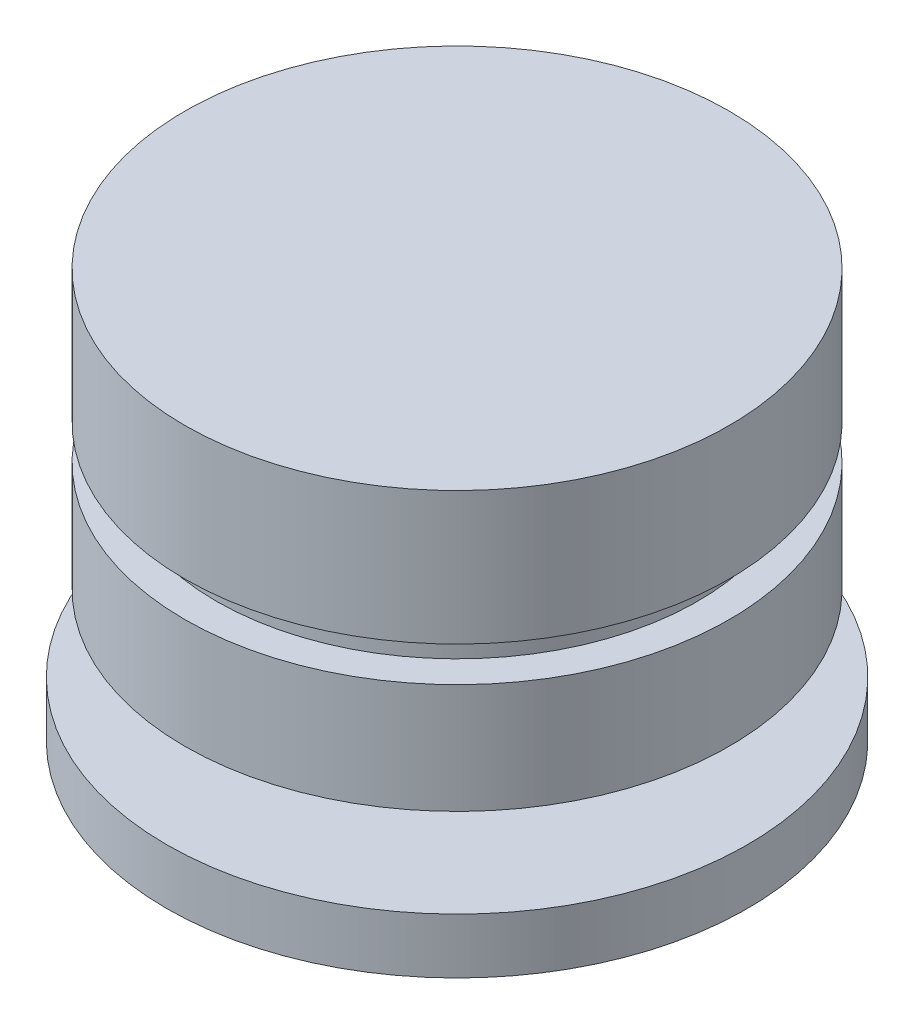
SolidWorks part; units mm, degrees
material "7075-T6 (SN)"
ref_plane "X-Y Datum" through (0, 0, 0) normal (0, 0, 1) x (1, 0, 0)
ref_plane "X-Z Datum" through (0, 0, 0) normal (0, 1, 0) x (1, 0, 0)
ref_plane "Y-Z Datum" through (0, 0, 0) normal (1, 0, 0) x (0, 0, -1)
sketch3d "3DSketch1"
  line L0 (0, 0, 0) -> (0, 50000, 0) construction
sketch "Mounting Plate SKETCH" plane through (0, 0, 0) normal (0, 1, 0) x (1, 0, 0)
  circle A0 centre (0, 0) radius 52.5
  dimension "mounting plate" = 105
extrude "Mount Plate" add sketch "Mounting Plate SKETCH" along normal blind 10
sketch "Hub-Rim Seat SKETCH" plane through (0, 0, 0) normal (0, -1, 0) x (1, 0, 0)
  circle A0 centre (0, 0) radius 27.435
  dimension "D1" = 54.87
sketch "Sketch7" plane through (0, 10, 0) normal (0, 1, 0) x (1, 0, 0)
  circle A0 centre (0, 0) radius 25.4
  dimension "D1" = 50.8
extrude "Boss-Extrude5" add sketch "Sketch7" along normal blind 13.749
sketch "Sketch6" [suppressed] plane through (0, 23.749, 0) normal (0, 1, 0) x (1, 0, 0)
  line L2 (0, -1000) -> (0, 49000) construction
  line L3 (-1000, 0) -> (49000, 0) construction
  line L20 (7.62, -45.2633) -> (12.7, -45.2633)
  line L21 (-7.62, -45.2633) -> (-12.7, -45.2633)
  line L22 (-43.0092, -16.0325) -> (-45.5492, -11.6331)
  line L23 (-35.3892, -29.2308) -> (-32.8492, -33.6302)
  line L24 (-35.3892, 29.2308) -> (-32.8492, 33.6302)
  line L25 (-43.0092, 16.0325) -> (-45.5492, 11.6331)
  line L26 (7.62, 45.2633) -> (12.7, 45.2633)
  line L27 (-7.62, 45.2633) -> (-12.7, 45.2633)
  line L28 (43.0092, 16.0325) -> (45.5492, 11.6331)
  line L29 (35.3892, 29.2308) -> (32.8492, 33.6302)
  line L30 (35.3892, -29.2308) -> (32.8492, -33.6302)
  line L31 (43.0092, -16.0325) -> (45.5492, -11.6331)
  line L32 (32.8492, -33.6302) -> (12.7, -45.2633)
  line L33 (45.5492, -11.6331) -> (45.5492, 11.6331)
  line L34 (32.8492, 33.6302) -> (12.7, 45.2633)
  line L35 (-12.7, 45.2633) -> (-32.8492, 33.6302)
  line L36 (-45.5492, -11.6331) -> (-45.5492, 11.6331)
  line L37 (-32.8492, -33.6302) -> (-12.7, -45.2633)
  arc A0 (7.62, -45.2633) -> (-7.62, -45.2633) centre (0, -45.2633) ccw
  circle A1 centre (0, 0) radius 45.2633 construction
  arc A7 (-35.3892, -29.2308) -> (-43.0092, -16.0325) centre (-39.1992, -22.6317) ccw
  arc A8 (-43.0092, 16.0325) -> (-35.3892, 29.2308) centre (-39.1992, 22.6317) ccw
  arc A9 (-7.62, 45.2633) -> (7.62, 45.2633) centre (0, 45.2633) ccw
  arc A10 (35.3892, 29.2308) -> (43.0092, 16.0325) centre (39.1992, 22.6317) ccw
  arc A11 (43.0092, -16.0325) -> (35.3892, -29.2308) centre (39.1992, -22.6317) ccw
  point P41 (0, 0)
  point P42 (0, 0)
  dimension "D2" = 7.62
  dimension "D1" = 90.5266
  dimension "D3" = 25.4
  dimension "D4" = 6
sketch "Drive Pin Circle" plane through (0, 10, 0) normal (0, 1, 0) x (1, 0, 0)
  circle A0 centre (0, 0) radius 40 construction
  dimension "D1" = 80
hole_wizard "Drive Pins" [suppressed] positions "Sketch10" profile "Sketch11" tap size "3/8-16" standard "ANSI Inch"
sketch "Sketch10" plane through (0, 0, 0) normal (0, 1, 0) x (1, 0, 0)
  circle A0 centre (0, 0) radius 40 construction
  point P0 (0, -40)
  point P12 (-40, 0)
  point P13 (0, 40)
  point P14 (40, 0)
  dimension "D1" = 4
cosmetic thread "Hole Thread5" [suppressed] parameters "D2"=9.525
cosmetic thread "Hole Thread6" [suppressed] parameters "D2"=9.525
cosmetic thread "Hole Thread7" [suppressed] parameters "D2"=9.525
cosmetic thread "Hole Thread8" [suppressed] parameters "D2"=9.525
sketch "Sketch11" plane through (0, 0, 40) normal (1, 0, 0) x (0, 0, -1)
  line L0 (0, 0) -> (0, 10)
  line L1 (0, 10) -> (3.9687, 10)
  line L2 (3.9687, 10) -> (3.9687, 0)
  line L5 (3.9687, 0) -> (0, 0)
  line L11 (0, -6.35) -> (0, 107.95) construction
  dimension "Thru Tap Drill Dia." = 7.9375
  dimension "Thru Tap Drill Depth" = 10
sketch "Sketch12" plane through (0, 23.749, 0) normal (0, 1, 0) x (1, 0, 0)
  circle A1 centre (0, 0) radius 49.2125
  dimension "D2" = 98.425
sketch "Sketch13" [suppressed] plane through (0, 0, 0) normal (0, -1, 0) x (1, 0, 0)
  arc A0 (-11.2502, 42.0194) -> (11.2502, 42.0194) centre (0, 40) cw
  circle A1 centre (0, 40) radius 3.9687 construction
  arc A2 (42.0194, 11.2502) -> (42.0194, -11.2502) centre (40, 0) cw
  arc A3 (11.2502, -42.0194) -> (-11.2502, -42.0194) centre (0, -40) cw
  arc A4 (-42.0194, -11.2502) -> (-42.0194, 11.2502) centre (-40, 0) cw
  arc A5 (-42.0194, 11.2502) -> (-11.2502, 42.0194) centre (-48.7508, 48.7508) ccw
  arc A6 (11.2502, 42.0194) -> (42.0194, 11.2502) centre (48.7508, 48.7508) ccw
  arc A7 (42.0194, -11.2502) -> (11.2502, -42.0194) centre (48.7508, -48.7508) ccw
  arc A8 (-11.2502, -42.0194) -> (-42.0194, -11.2502) centre (-48.7508, -48.7508) ccw
  circle A9 centre (40, 0) radius 3.9687 construction
  circle A11 centre (0, 0) radius 52.5 construction
  circle A12 centre (0, 0) radius 52.5
  point P17 (0, 0)
  dimension "D1" = 11.43
  dimension "D4" = 38.1
  dimension "D5" = 38.1
  dimension "D6" = 38.1
  dimension "D7" = 38.1
  dimension "D3" = 4
extrude "Cut-Extrude3" [suppressed] cut sketch "Sketch13" against normal up to next
sketch3d "3DSketch3"
  point P0 (0, 22, -205.74)
  dimension "D1" = 205.74
  dimension "D2" = 22
extrude "Boss-Extrude6" add sketch "Sketch12" along normal blind 50.231
sketch "Sketch15" plane through (0, 0, 0) normal (1, 0, 0) x (0, 0, -1)
  line L0 (0, 0) -> (0, -50000) construction
  line L1 (0, 0) -> (50000, 0) construction
  line L3 (49.2125, 49.944) -> (43.4975, 49.944)
  line L4 (49.2125, 49.944) -> (49.2125, 43.594)
  line L5 (49.2125, 43.594) -> (43.4975, 43.594)
  line L6 (43.4975, 49.944) -> (43.4975, 43.594)
  line L7 (49.2125, 49.944) -> (43.4975, 43.594) construction
  line L8 (49.2125, 43.594) -> (43.4975, 49.944) construction
  line L9 (-49.2125, 23.749) -> (49.2125, 23.749) construction
  point P5 (46.355, 46.769)
  dimension "D1" = 6.35
  dimension "D2" = 19.845
  dimension "D3" = 98.425
  dimension "D4" = 86.995
revolve "Cut-Revolve3" cut sketch "Sketch15" angle 360 about L0
extrude "Boss-Extrude7" [suppressed] add sketch "Hub-Rim Seat SKETCH" along normal blind 3.175
